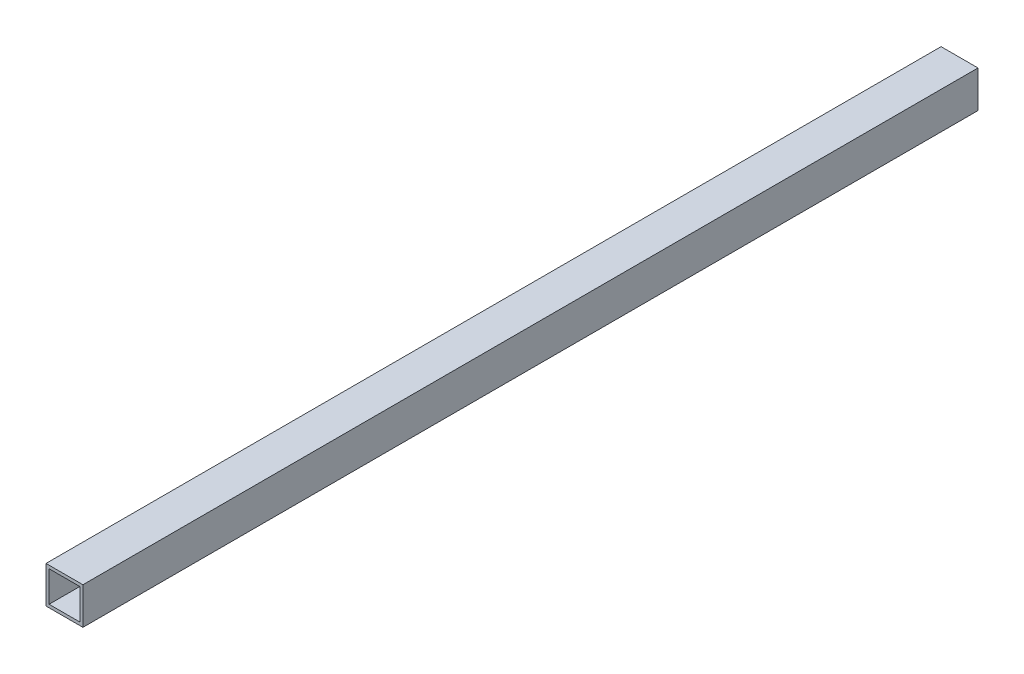
SolidWorks part; units mm, degrees
ref_plane "Front Plane" through (0, 0, 0) normal (0, 0, 1) x (1, 0, 0)
ref_plane "Top Plane" through (0, 0, 0) normal (0, 1, 0) x (1, 0, 0)
ref_plane "Right Plane" through (0, 0, 0) normal (1, 0, 0) x (0, 0, -1)
sketch "Sketch1" plane through (0, 0, 830.698) normal (0, 0, -1) x (-1, 0, 0)
  line L0 (264.9679, 3.9434) -> (280.8429, 3.9434)
  line L1 (263.3804, 5.5309) -> (282.4304, 5.5309)
  line L2 (263.3804, 5.5309) -> (263.3804, -13.5191)
  line L3 (263.3804, -13.5191) -> (282.4304, -13.5191)
  line L4 (282.4304, 5.5309) -> (282.4304, -13.5191)
  line L5 (280.8429, 3.9434) -> (280.8429, -11.9316)
  line L6 (264.9679, -11.9316) -> (280.8429, -11.9316)
  line L7 (264.9679, 3.9434) -> (264.9679, -11.9316)
  dimension "D1" = 1.5875
  dimension "D2" = 19.05
extrude "Boss-Extrude1" add sketch "Sketch1" along normal up to surface (461.9 mm away)
ref_plane "Plane1" through (-272.9054, 0, 0) normal (-1, 0, 0) x (0, 0, 1)
